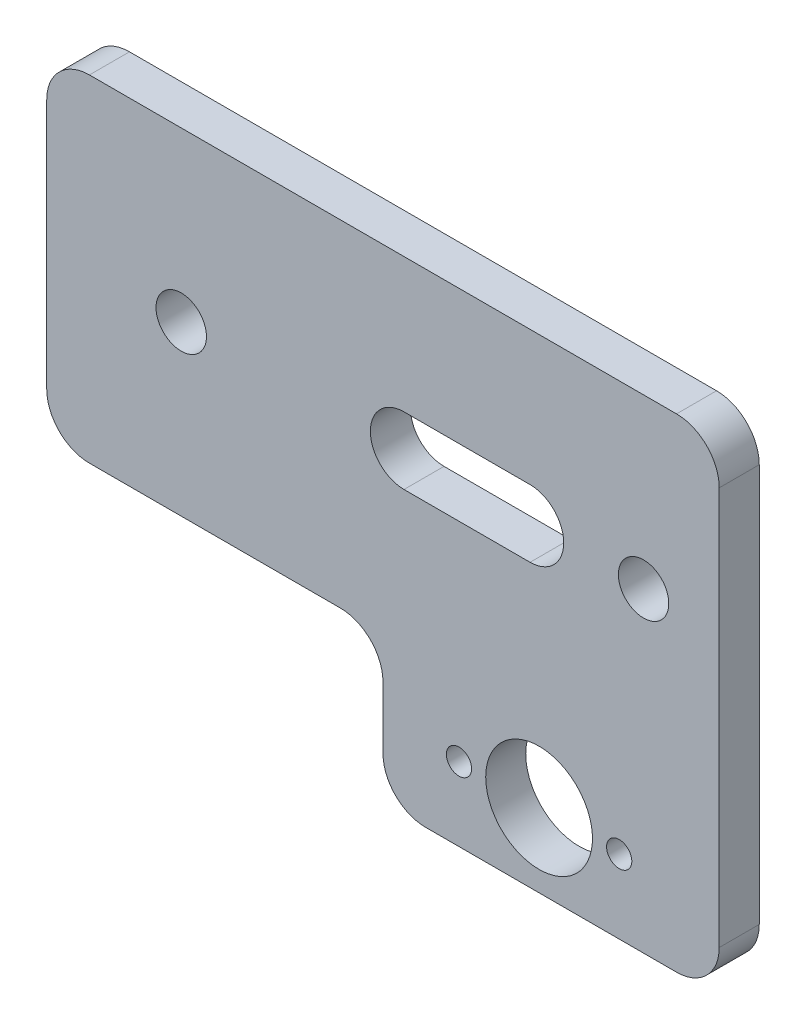
SolidWorks part; units mm, degrees
ref_plane "Front Plane" through (0, 0, 0) normal (0, 0, 1) x (1, 0, 0)
ref_plane "Top Plane" through (0, 0, 0) normal (0, 1, 0) x (1, 0, 0)
ref_plane "Right Plane" through (0, 0, 0) normal (1, 0, 0) x (0, 0, -1)
sketch "Sketch1" plane through (0, 0, 0) normal (0, 0, 1) x (1, 0, 0)
  line L0 (490.9844, 2.8169) -> (505.9844, 2.8169) construction
  line L1 (528.4844, 22.8169) -> (448.4844, 22.8169)
  line L2 (528.4844, 22.8169) -> (528.4844, -34.7031)
  line L3 (528.4844, -34.7031) -> (488.4844, -34.7031)
  line L4 (488.4844, -17.1831) -> (488.4844, -34.7031)
  line L5 (490.9844, 6.8169) -> (505.9844, 6.8169)
  line L6 (490.9844, -1.1831) -> (505.9844, -1.1831)
  line L8 (448.4844, 22.8169) -> (448.4844, -17.1831)
  line L9 (448.4844, -17.1831) -> (488.4844, -17.1831)
  circle A0 centre (507.0544, -25.9431) radius 6.35
  arc A1 (490.9844, 6.8169) -> (490.9844, -1.1831) centre (490.9844, 2.8169) ccw
  arc A2 (505.9844, -1.1831) -> (505.9844, 6.8169) centre (505.9844, 2.8169) ccw
  circle A3 centre (464.4844, 2.8169) radius 3
  circle A4 centre (519.4844, 2.8169) radius 3
  point P3 (516.5844, -25.9431)
  point P4 (497.5244, -25.9431)
  point P10 (498.4844, 2.8169)
  dimension "D2" = 15
  dimension "D5" = 20
  dimension "D7" = 16
  dimension "D1" = 40
  dimension "D3" = 20
  dimension "D4" = 30
  dimension "D6" = 9
  dimension "D8" = 40
  dimension "D9" = 20
  dimension "D10" = 21.43
  dimension "D11" = 8.76
  dimension "D12" = 48.76
  dimension "D13" = 80
  dimension "D14" = 9.53
  dimension "D15" = 9.53
extrude "Boss-Extrude1" add sketch "Sketch1" along normal blind 4.7625
fillet "Fillet1" radius 5.08 6 edges at (528.4844, 22.8169, 2.3813) (488.4844, -34.7031, 2.3813) (528.4844, -34.7031, 2.3813) (448.4844, 22.8169, 2.3813) (448.4844, -17.1831, 2.3813) (488.4844, -17.1831, 2.3813)
hole_wizard "Ø3.0 (3) Diameter Hole1" positions "Sketch5" profile "Sketch4" hole size "Ø3.0" standard "ANSI Metric"
sketch "Sketch5" plane through (0, 0, 0) normal (0, 0, -1) x (-1, 0, 0)
  point P0 (-497.5244, -25.9431)
  point P3 (-516.5844, -25.9431)
sketch "Sketch4" plane through (497.5244, -25.9431, 0) normal (1, 0, 0) x (0, 1, 0)
  line L0 (0, 0) -> (0, 26.3013)
  line L1 (0, 26.3013) -> (1.5, 25.4)
  line L2 (1.5, 25.4) -> (1.5, 0)
  line L5 (1.5, 0) -> (0, 0)
  line L10 (0, 26.3013) -> (-1.5, 25.4) construction
  line L11 (0, -6.35) -> (0, 107.95) construction
  dimension "Hole Dia." = 3
  dimension "Hole Depth" = 25.4
  dimension "Drill Angle" = 118
